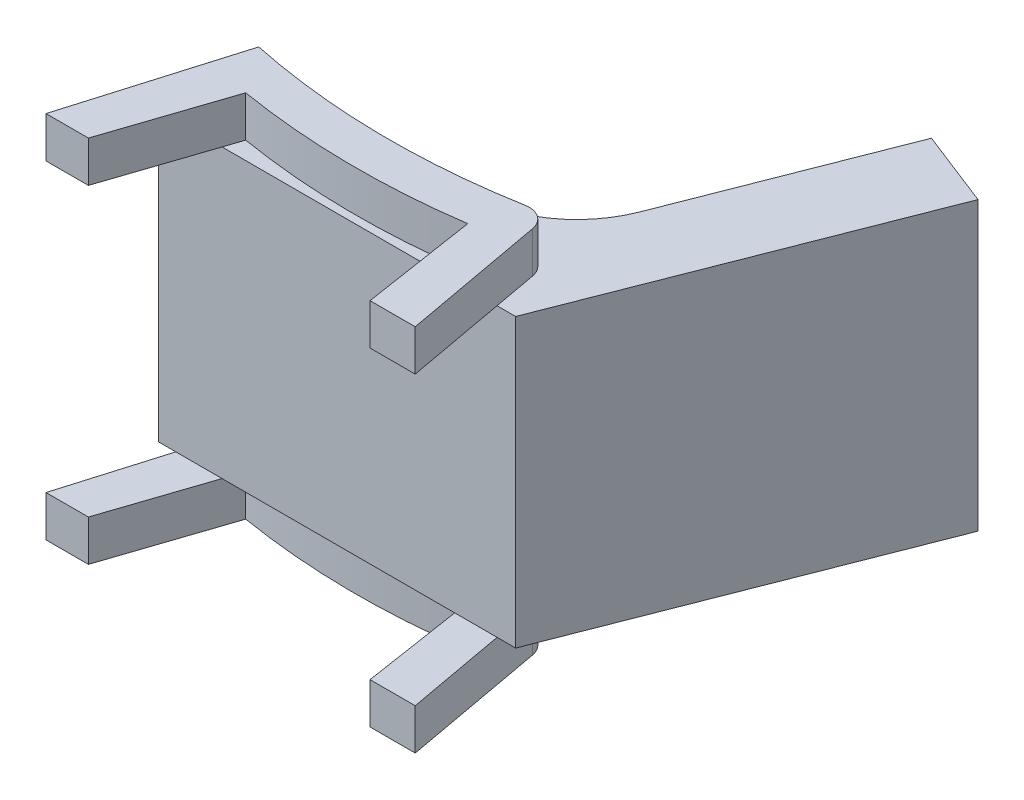
SolidWorks part; units mm, degrees
ref_plane "Front Plane" through (0, 0, 0) normal (0, 0, 1) x (1, 0, 0)
ref_plane "Top Plane" through (0, 0, 0) normal (0, 1, 0) x (1, 0, 0)
ref_plane "Right Plane" through (0, 0, 0) normal (1, 0, 0) x (0, 0, -1)
sketch "Sketch1" plane through (0, 0, 0) normal (0, 1, 0) x (1, 0, 0)
  line L0 (-76.6869, 0) -> (162.3161, 0) construction
  line L2 (-61.5001, 0) -> (25.4999, 0)
  line L3 (-61.5001, 0) -> (-61.5001, 20)
  line L4 (-61.5001, 20) -> (-6.5908, 20)
  line L5 (25.4999, 0) -> (25.4999, 16.3942)
  line L6 (25.4999, 0) -> (57.1748, 81.029)
  line L7 (18.5561, 37.1698) -> (38.5475, 88.3106)
  line L8 (57.1748, 81.029) -> (38.5475, 88.3106)
  arc A0 (18.5561, 37.1698) -> (-6.5908, 20) centre (-6.5908, 47) cw
  dimension "D1" = 27
  dimension "D2" = 87
  dimension "D3" = 87
  dimension "D4" = 20
  dimension "D5" = 20
extrude "Boss-Extrude1" add sketch "Sketch1" along normal blind 70
sketch "Sketch2" plane through (0, 70, 0) normal (0, 1, 0) x (1, 0, 0)
  line L1 (-52.7128, 15.5887) -> (-64.565, -24.4113)
  line L2 (-44.6137, 4.3159) -> (-54.2335, -24.4113)
  line L5 (18.1215, 15.5887) -> (25.435, -24.4113)
  line L6 (10.0658, 3.753) -> (14.4189, -24.4113)
  line L8 (-64.565, -24.4113) -> (-54.2335, -24.4113)
  line L9 (14.4189, -24.4113) -> (25.435, -24.4113)
  arc A0 (-52.7128, 15.5887) -> (18.1215, 15.5887) centre (-17.2957, 184.9245) ccw
  arc A1 (-44.6137, 4.3159) -> (10.0658, 3.753) centre (-15.4614, 180.1048) ccw
  point P12 (-17.2957, 1.9245)
  point P13 (-17.2957, 11.9245)
  dimension "D1" = 90
  dimension "D6" = 173
  dimension "D2" = 183
  dimension "D3" = 40
  dimension "D4" = 40
  dimension "D5" = 10
extrude "Boss-Extrude2" add sketch "Sketch2" along normal blind 10
fillet "Fillet1" radius 5 1 edges at (18.1215, 75, -15.5887)
ref_plane "Plane1" through (0, 35, 0) normal (0, 1, 0) x (1, 0, 0)
mirror "Mirror1" about plane through (0, 35, 0) normal (0, 1, 0) of "Fillet1", "Boss-Extrude2"
